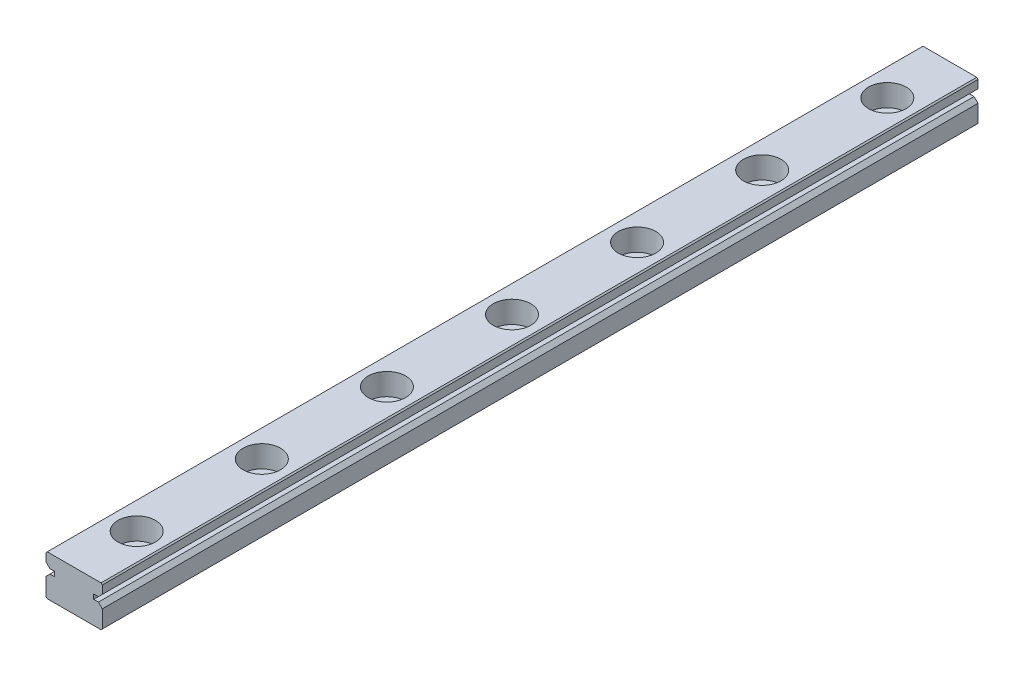
SolidWorks part; units mm, degrees
material "不锈钢 (铁素体)"
ref_plane "前视基准面" through (0, 0, 0) normal (0, 0, 1) x (1, 0, 0)
ref_plane "上视基准面" through (0, 0, 0) normal (0, 1, 0) x (1, 0, 0)
ref_plane "右视基准面" through (0, 0, 0) normal (1, 0, 0) x (0, 0, -1)
sketch "草图1" plane through (0, 0, 0) normal (0, 0, 1) x (1, 0, 0)
  point P0 (0, 0)
  line B0 (4.3, 0) -> (4.5, 0.2)
  line B1 (-4.5, 0.2) -> (-4.3, 0)
  line B2 (-4.3, 0) -> (4.3, 0)
  line B3 (-4.5, 3) -> (-4.5, 0.2)
  line B4 (4.5, 0.2) -> (4.5, 3)
  line B5 (4.5, 3) -> (3.875, 3.625)
  line B6 (3.875, 3.625) -> (3.125, 3.625)
  line B7 (3.125, 3.625) -> (3.125, 4.375)
  line B8 (3.125, 4.375) -> (3.875, 4.375)
  line B9 (3.875, 4.375) -> (4.5, 5)
  line B10 (4.5, 5) -> (4.5, 6.3)
  line B11 (-4.5, 6.3) -> (-4.5, 5)
  line B12 (-4.5, 5) -> (-3.875, 4.375)
  line B13 (-3.875, 4.375) -> (-3.125, 4.375)
  line B14 (-3.125, 4.375) -> (-3.125, 3.625)
  line B15 (-3.125, 3.625) -> (-3.875, 3.625)
  line B16 (-3.875, 3.625) -> (-4.5, 3)
  line B17 (-4.3, 6.5) -> (-4.5, 6.3)
  line B18 (4.5, 6.3) -> (4.3, 6.5)
  line B19 (4.3, 6.5) -> (-4.3, 6.5)
sketch_block_instance "MGNR9导轨截面-1"
sketch_block "MGNR9导轨截面"
extrude "凸台-拉伸1" add sketch "草图1" along normal blind 140
hole_wizard "打孔尺寸(%根据)内六角圆柱头螺钉的类型1" positions "草图2" profile "草图3" counterbore size "M3" standard "GB" end condition through all
sketch "草图2" plane through (0, 6.5, 0) normal (0, 1, 0) x (1, 0, 0)
  point P0 (0, -10)
  dimension "D1" = 10
sketch "草图3" plane through (0, 6.5, 10) normal (1, 0, 0) x (0, 0, 1)
  line L0 (0, 0) -> (0, 6.5)
  line L1 (0, 6.5) -> (1.75, 6.5)
  line L3 (1.75, 6.5) -> (1.75, 3.5)
  line L4 (1.75, 3.5) -> (3, 3.5)
  line L5 (3, 3.5) -> (3, 0)
  line L7 (3, 0) -> (0, 0)
  line L11 (0, -6.35) -> (0, 107.95) construction
  dimension "通孔孔直径" = 3.5
  dimension "通孔孔深度" = 6.5
  dimension "柱形沉头孔直径" = 6
  dimension "柱形沉头孔深度" = 3.5
pattern_linear "阵列(线性)1" count 7 spacing 20 along (0, 0, 1) of "打孔尺寸(%根据)内六角圆柱头螺钉的类型1"
